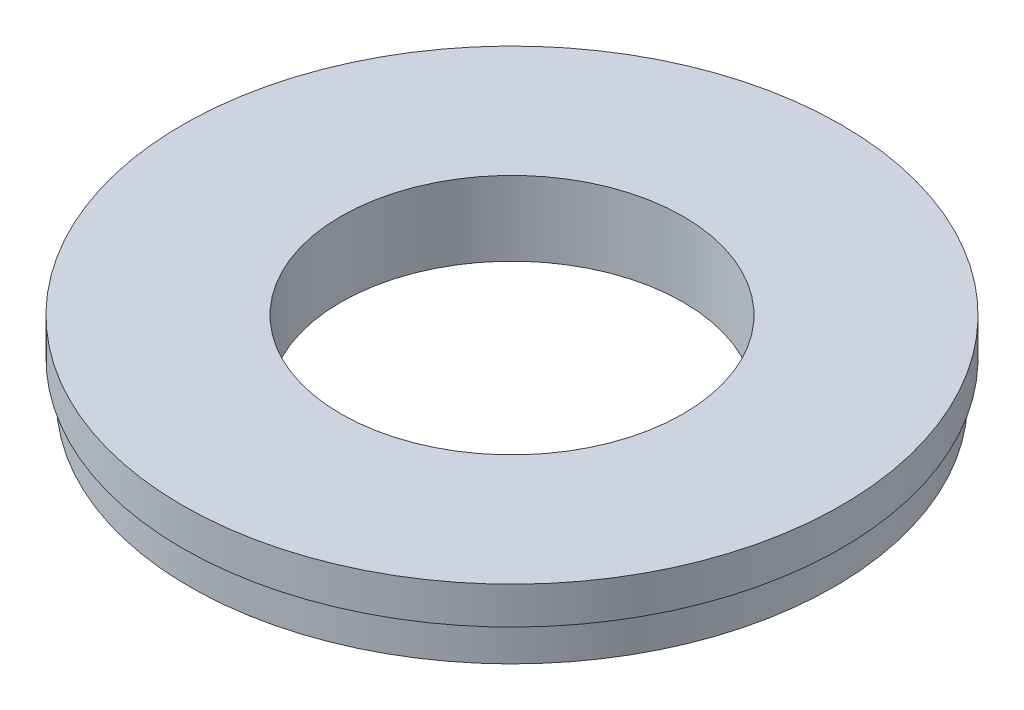
SolidWorks part; units mm, degrees
ref_plane "Front Plane" through (0, 0, 0) normal (0, 0, 1) x (1, 0, 0)
ref_plane "Top Plane" through (0, 0, 0) normal (0, 1, 0) x (1, 0, 0)
ref_plane "Right Plane" through (0, 0, 0) normal (1, 0, 0) x (0, 0, -1)
sketch "Sketch1" plane through (0, 0, 0) normal (0, 0, 1) x (1, 0, 0)
  line L0 (0, 0) -> (0, 11.938) construction
  line L1 (27.5, 11.938) -> (52.959, 11.938)
  line L2 (52.959, 11.938) -> (52.959, 5.969)
  line L3 (27.5, 0) -> (51.7652, 0)
  line L4 (52.959, 5.969) -> (51.7652, 5.969)
  line L5 (51.7652, 5.969) -> (51.7652, 0)
  line L6 (27.5, 11.938) -> (27.5, 0)
  line L7 (0, 11.938) -> (27.5, 11.938) construction
  line L8 (0, 0) -> (27.5, 0) construction
  dimension "D1" = 52.959
  dimension "D2" = 11.938
  dimension "D3" = 1.1938
  dimension "D4" = 5.969
  dimension "D5" = 27.5
revolve "Revolve1" add sketch "Sketch1" angle 360 about L0
